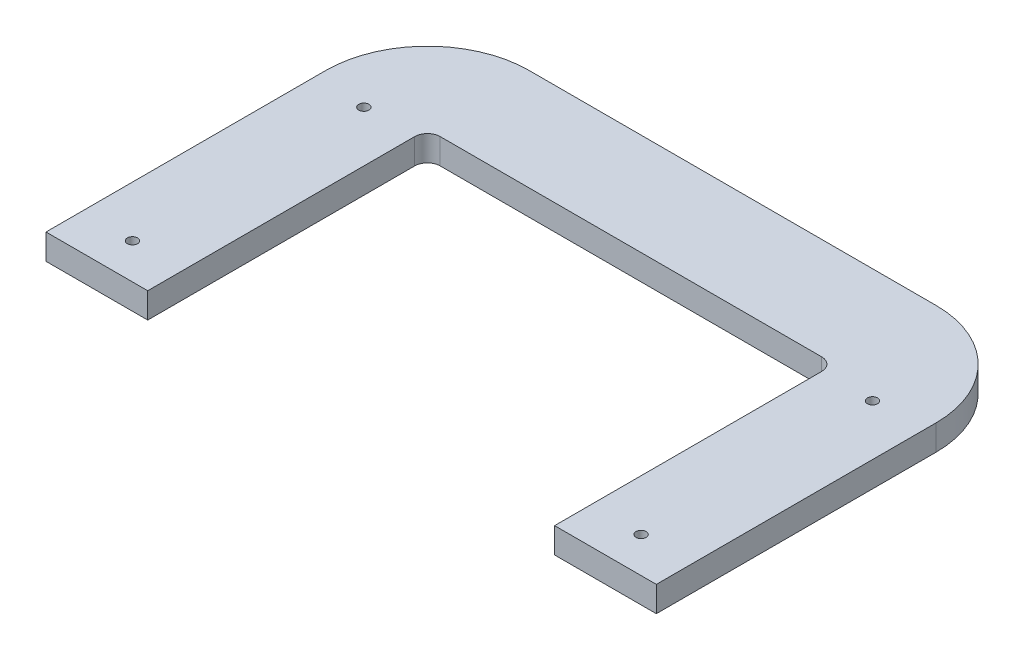
SolidWorks part; units mm, degrees
ref_plane "前视基准面" through (0, 0, 0) normal (0, 0, 1) x (1, 0, 0)
ref_plane "上视基准面" through (0, 0, 0) normal (0, 1, 0) x (1, 0, 0)
ref_plane "右视基准面" through (0, 0, 0) normal (1, 0, 0) x (0, 0, -1)
other "Configuration Table"
sketch "草图1" plane through (0, 0, 0) normal (0, 1, 0) x (1, 0, 0)
  line L1 (-120, 142.1256) -> (-120, -7.8744)
  line L2 (-80, 102.1256) -> (-80, -7.8744)
  line L3 (0, 67.2258) -> (0, -47.8024) construction
  line L4 (-120, -7.8744) -> (-80, -7.8744)
  line L5 (120, 142.1256) -> (120, -7.8744)
  line L6 (120, -7.8744) -> (80, -7.8744)
  line L7 (80, 102.1256) -> (80, -7.8744)
  line L8 (-80, 102.1256) -> (80, 102.1256)
  line L10 (-120, 142.1256) -> (120, 142.1256)
  line L11 (-100, -7.8744) -> (-100, 153.4587) construction
  circle A0 centre (-100, 97.1256) radius 2
  circle A1 centre (100, 97.1256) radius 2
  circle A2 centre (-100, 6.1256) radius 2
  circle A3 centre (100, 6.1256) radius 2
  dimension "D5" = 45
  dimension "D6" = 91
  dimension "D7" = 4
  dimension "D1" = 40
  dimension "D2" = 150
  dimension "D3" = 40
  dimension "D4" = 240
extrude "凸台-拉伸1" add sketch "草图1" along normal blind 10
fillet "圆角1" radius 40 2 edges at (120, 5, -142.1256) (-120, 5, -142.1256)
fillet "圆角2" radius 5 2 edges at (80, 5, -102.1256) (-80, 5, -102.1256)
